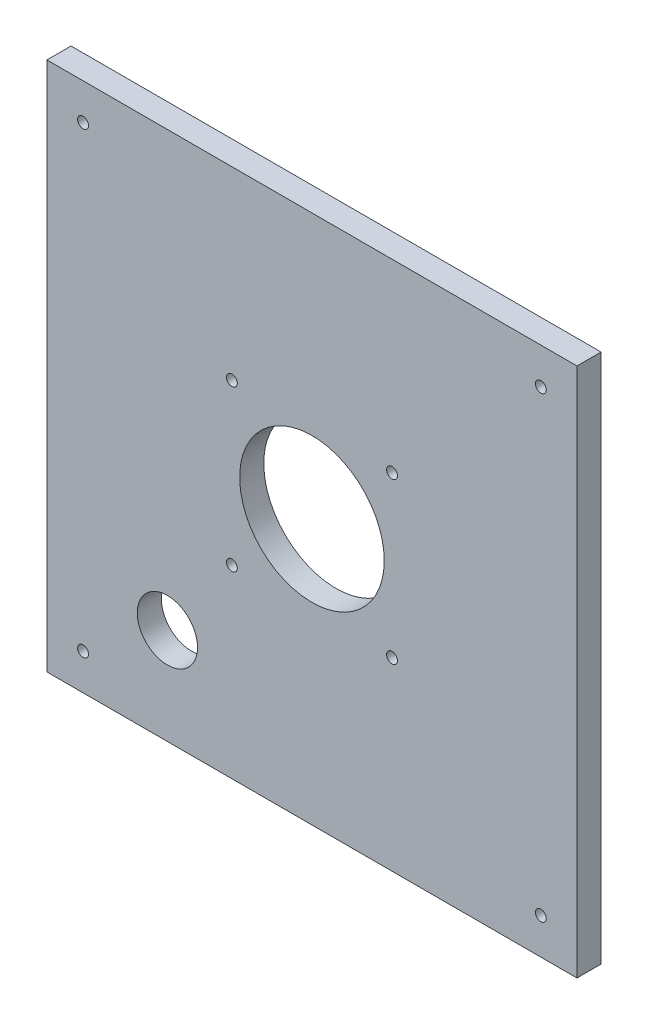
SolidWorks part; units mm, degrees
material "Aleación 6061"
ref_plane "Alzado" through (0, 0, 0) normal (0, 0, 1) x (1, 0, 0)
ref_plane "Planta" through (0, 0, 0) normal (0, 1, 0) x (1, 0, 0)
ref_plane "Vista lateral" through (0, 0, 0) normal (1, 0, 0) x (0, 0, -1)
sketch "Sk_Placa" plane through (0, 0, 0) normal (0, 0, 1) x (1, 0, 0)
  line L1 (-110, -110) -> (110, -110)
  line L2 (-110, -110) -> (-110, 110)
  line L3 (-110, 110) -> (110, 110)
  line L4 (110, -110) -> (110, 110)
  line L5 (-110, -110) -> (110, 110) construction
  line L6 (-110, 110) -> (110, -110) construction
  point P0 (0, 0)
  dimension "D1" = 220
  dimension "D2" = 220
extrude "Placa" add sketch "Sk_Placa" along normal blind 10
sketch "Sk_Paso_cables" plane through (0, 0, 0) normal (0, 0, 1) x (1, 0, 0)
  circle A0 centre (0, 0) radius 30
  dimension "D1" = 60
extrude "Paso_cables" cut sketch "Sk_Paso_cables" along normal blind 10
sketch "Sk_Pasantes_M4_pedestal" plane through (0, 0, 0) normal (0, 0, 1) x (1, 0, 0)
  circle A0 centre (33.234, 33.234) radius 2.25
  circle A1 centre (-33.234, 33.234) radius 2.25
  circle A2 centre (-33.234, -33.234) radius 2.25
  circle A3 centre (33.234, -33.234) radius 2.25
  dimension "D1" = 4.5
  dimension "D4" = 4.5
  dimension "D7" = 4.5
  dimension "D10" = 4.5
  dimension "D2" = 33.234
  dimension "D3" = 33.234
  dimension "D5" = 33.234
  dimension "D6" = 33.234
  dimension "D8" = 33.234
  dimension "D9" = 33.234
  dimension "D11" = 33.234
  dimension "D12" = 33.234
extrude "Pasantes_M4_pedestal" cut sketch "Sk_Pasantes_M4_pedestal" along normal blind 10
sketch "Sk_Cajas_M4_inferiores" plane through (0, 0, 0) normal (0, 0, 1) x (1, 0, 0)
  circle A0 centre (33.234, 33.234) radius 4
  circle A1 centre (-33.234, 33.234) radius 4
  circle A2 centre (-33.234, -33.234) radius 4
  circle A3 centre (33.234, -33.234) radius 4
  dimension "D1" = 8
  dimension "D4" = 8
  dimension "D7" = 8
  dimension "D10" = 8
  dimension "D2" = 33.234
  dimension "D3" = 33.234
  dimension "D5" = 33.234
  dimension "D6" = 33.234
  dimension "D8" = 33.234
  dimension "D9" = 33.234
  dimension "D11" = 33.234
  dimension "D12" = 33.234
extrude "Cajas_M4_inferiores" cut sketch "Sk_Cajas_M4_inferiores" along normal blind 4.5
sketch "Sk_Pasantes_M4_separadores_caja" plane through (0, 0, 0) normal (0, 0, 1) x (1, 0, 0)
  circle A0 centre (-95, -95) radius 2.25
  circle A1 centre (-95, 95) radius 2.25
  circle A2 centre (95, -95) radius 2.25
  circle A3 centre (95, 95) radius 2.25
  dimension "D1" = 4.5
  dimension "D4" = 4.5
  dimension "D7" = 4.5
  dimension "D10" = 4.5
  dimension "D2" = 95
  dimension "D3" = 95
  dimension "D5" = 95
  dimension "D6" = 95
  dimension "D8" = 95
  dimension "D9" = 95
  dimension "D11" = 95
  dimension "D12" = 95
extrude "Pasantes_M4_separadores_caja" cut sketch "Sk_Pasantes_M4_separadores_caja" along normal blind 10
sketch "Sk_Paso_cables_caja" plane through (0, 0, 0) normal (0, 0, 1) x (1, 0, 0)
  circle A0 centre (-60, -70) radius 12.5
  dimension "D1" = 25
  dimension "D2" = 60
  dimension "D3" = 70
extrude "Paso_cables_caja" cut sketch "Sk_Paso_cables_caja" along normal blind 10
